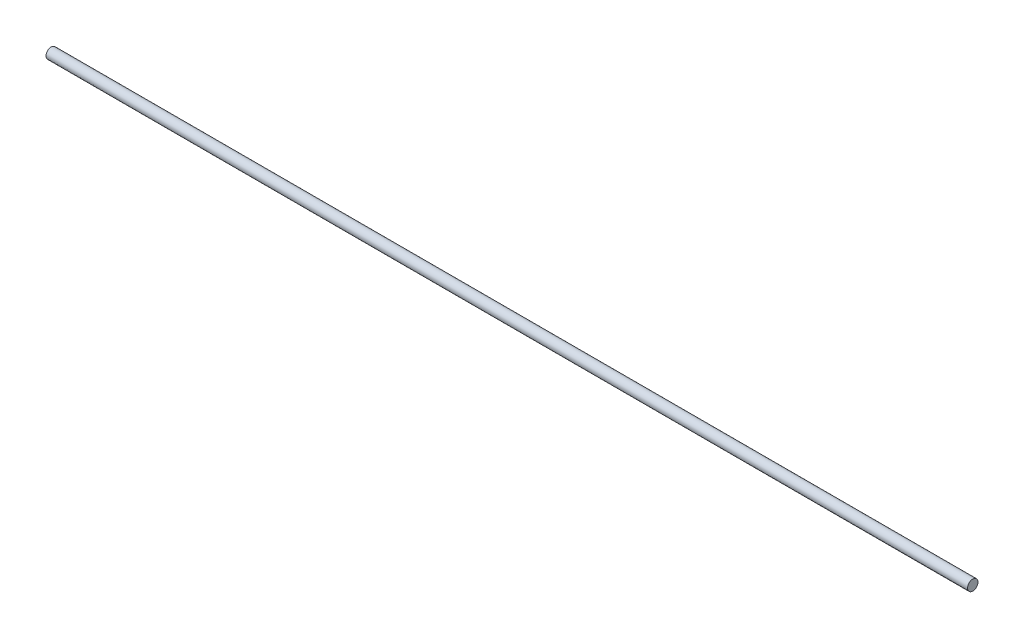
SolidWorks part; units mm, degrees
material "6061 Alloy"
ref_plane "Front Plane" through (0, 0, 0) normal (1, 0, 0) x (0, 1, 0)
ref_plane "Top Plane" through (0, 0, 0) normal (0, 0, 1) x (0, 1, 0)
ref_plane "Right Plane" through (0, 0, 0) normal (0, 1, 0) x (-1, 0, 0)
sketch "Sketch1" plane through (0, 0, 0) normal (1, 0, 0) x (0, 1, 0)
  circle A0 centre (0, 0) radius 6.35
  dimension "D1" = 12.7
extrude "Boss-Extrude1" add sketch "Sketch1" against normal blind 1122.1376 contours A0
equation "\"Deflection\"= 0.009"
equation "\"Force\"= 400"
equation "\"Yield\"= 40000"
equation "\"Elastic\"= 10000000"
equation "\"Diameter\"= .5"
equation "\"Area\"= ( pi / 4 ) * ( \"Diameter\" ) ^ 2"
equation "\"Length\"= \"Deflection\" * \"Area\" * \"Elastic\" / \"Force\""
equation "\"D1@Sketch1\"= \"Diameter\""
equation "\"D1@Boss-Extrude1\"=\"Length\""
